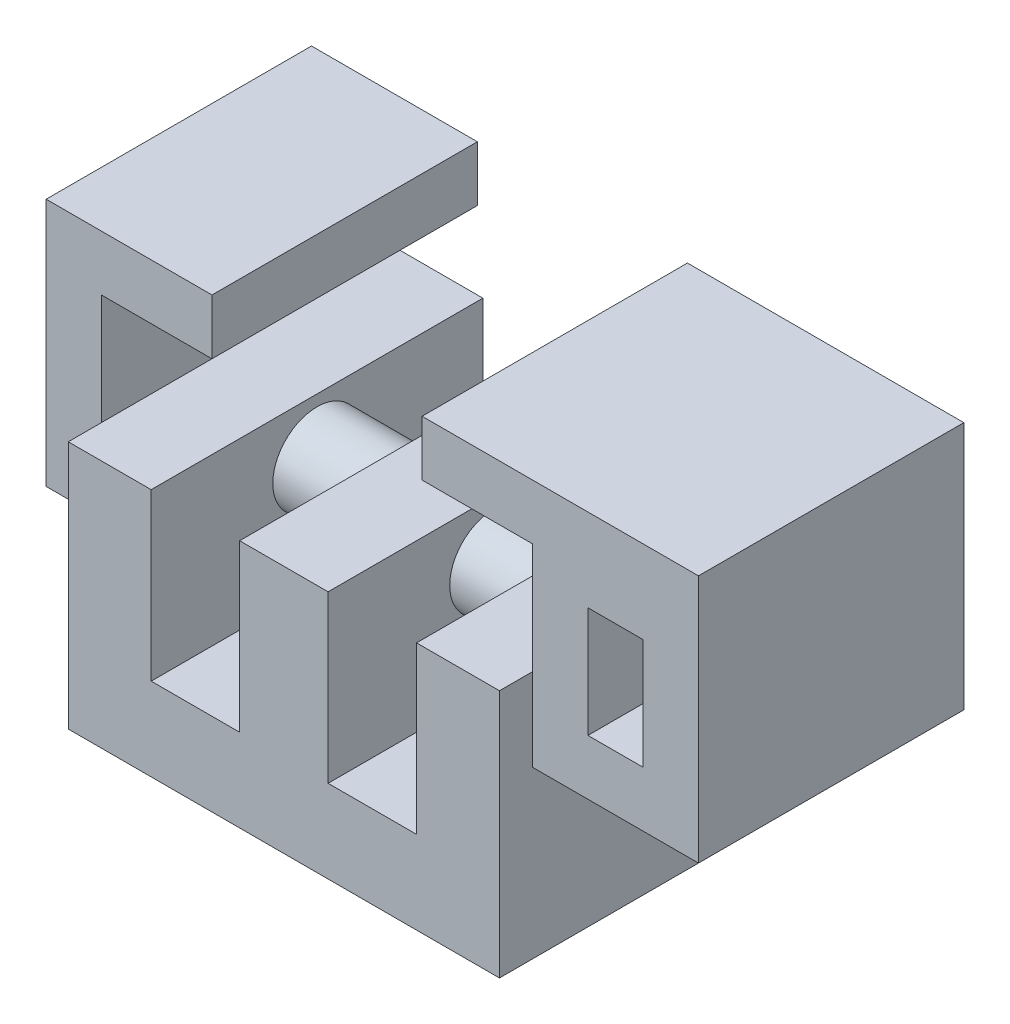
SolidWorks part; units mm, degrees
ref_plane "Plan de face" through (0, 0, 0) normal (0, 0, 1) x (1, 0, 0)
ref_plane "Plan de dessus" through (0, 0, 0) normal (0, 1, 0) x (1, 0, 0)
ref_plane "Plan de droite" through (0, 0, 0) normal (1, 0, 0) x (0, 0, -1)
sketch "Esquisse1" plane through (0, 0, 0) normal (0, 1, 0) x (1, 0, 0)
  line L1 (-19.5, -15) -> (19.5, -15)
  line L2 (-19.5, -15) -> (-19.5, 15)
  line L3 (-19.5, 15) -> (19.5, 15)
  line L4 (19.5, -15) -> (19.5, 15)
  line L5 (-19.5, -15) -> (19.5, 15) construction
  line L6 (-19.5, 15) -> (19.5, -15) construction
  point P0 (0, 0)
  dimension "D1" = 39
  dimension "D2" = 30
extrude "Boss.-Extru.1" add sketch "Esquisse1" along normal blind 7.5 and the other way blind 15
sketch "Esquisse2" plane through (0, 0, 0) normal (0, 1, 0) x (1, 0, 0)
  line L0 (-19.5, 0) -> (-42.4216, 0) construction
  line L1 (-19.5, 15) -> (-19.5, -15) construction
  line L2 (-19.5, 0) -> (-19.5, 12)
  line L3 (-19.5, 12) -> (-24.5, 12)
  line L4 (-24.5, 12) -> (-24.5, -12)
  line L5 (-24.5, -12) -> (-19.5, -12)
  line L6 (-19.5, -12) -> (-19.5, 0)
  line L7 (19.5, 0) -> (36.2396, 0) construction
  line L8 (19.5, -15) -> (19.5, 15) construction
  line L9 (19.5, 0) -> (19.5, 12)
  line L10 (19.5, 12) -> (24.5, 12)
  line L11 (24.5, 12) -> (24.5, -12)
  line L12 (24.5, -12) -> (19.5, -12)
  line L13 (19.5, 0) -> (19.5, -12)
  dimension "D1" = 12
  dimension "D2" = 12
  dimension "D3" = 5
  dimension "D4" = 12
  dimension "D5" = 12
  dimension "D6" = 5
extrude "Boss.-Extru.2" add sketch "Esquisse2" along normal blind 22.5
sketch "Esquisse3" plane through (-19.5, 0, 0) normal (1, 0, 0) x (0, 0, -1)
  line L0 (-12, 22.5) -> (-12, 0) construction
  line L1 (12, 22.5) -> (-12, 22.5)
  line L2 (12, 22.5) -> (12, 17.5)
  line L3 (12, 17.5) -> (-12, 17.5)
  line L4 (-12, 22.5) -> (-12, 17.5)
  dimension "D1" = 5
extrude "Boss.-Extru.3" add sketch "Esquisse3" along normal blind 10
sketch "Esquisse4" plane through (19.5, 0, 0) normal (-1, 0, 0) x (0, 0, 1)
  line L0 (12, 22.5) -> (12, 0) construction
  line L1 (-12, 22.5) -> (12, 22.5)
  line L2 (-12, 22.5) -> (-12, 17.5)
  line L3 (-12, 17.5) -> (12, 17.5)
  line L4 (12, 22.5) -> (12, 17.5)
  dimension "D1" = 5
extrude "Boss.-Extru.4" add sketch "Esquisse4" along normal blind 10
sketch "Esquisse5" plane through (24.5, 0, 0) normal (1, 0, 0) x (0, 0, -1)
  line L5 (-12, 22.5) -> (12, 22.5)
  line L6 (-12, 22.5) -> (-12, 0)
  line L7 (-12, 0) -> (12, 0)
  line L8 (12, 22.5) -> (12, 0)
extrude "Boss.-Extru.5" add sketch "Esquisse5" along normal blind 10
sketch "Esquisse6" plane through (0, 0, -12) normal (0, 0, -1) x (-1, 0, 0)
  line L0 (-34.5, 22.5) -> (-29.5, 22.5) construction
  line L1 (-34.5, 22.5) -> (-9.5, 22.5) construction
  line L2 (-29.5, 22.5) -> (-29.5, 15) construction
  line L4 (-29.5, 15) -> (-24.5, 15)
  line L5 (-29.5, 15) -> (-29.5, 5)
  line L6 (-29.5, 5) -> (-24.5, 5)
  line L7 (-24.5, 15) -> (-24.5, 5)
  dimension "D1" = 5
  dimension "D2" = 5
  dimension "D3" = 7.5
  dimension "D4" = 10
extrude "Enlèv. mat.-Extru.1" cut sketch "Esquisse6" against normal through all
sketch "Esquisse7" plane through (0, 7.5, 0) normal (0, 1, 0) x (1, 0, 0)
  line L0 (-19.5, 15) -> (-12, 15) construction
  line L1 (19.5, 15) -> (-19.5, 15) construction
  line L2 (-12, 15) -> (-4, 15) construction
  line L3 (-4, 15) -> (4, 15) construction
  line L4 (4, 15) -> (12, 15) construction
  line L5 (12, 15) -> (19.5, 15) construction
  line L6 (-19.5, -15) -> (19.5, -15) construction
  line L7 (-12, 15) -> (-4, 15)
  line L8 (-12, 15) -> (-12, -15)
  line L9 (-12, -15) -> (-4, -15)
  line L10 (-4, 15) -> (-4, -15)
  line L12 (4, 15) -> (12, 15)
  line L13 (4, 15) -> (4, -15)
  line L14 (4, -15) -> (12, -15)
  line L15 (12, 15) -> (12, -15)
  dimension "D1" = 7.5
  dimension "D2" = 8
  dimension "D3" = 8
  dimension "D4" = 7.5
extrude "Enlèv. mat.-Extru.2" cut sketch "Esquisse7" against normal blind 15
sketch "Esquisse8" plane through (-12, 0, 0) normal (1, 0, 0) x (0, 0, -1)
  line L0 (0, -7.509) -> (0, 2.491) construction
  circle A1 centre (0, 2.491) radius 4
  dimension "D2" = 8
  dimension "D1" = 10
extrude "Boss.-Extru.6" add sketch "Esquisse8" along normal blind 25
sketch "Esquisse9" plane through (0, -15, 0) normal (0, -1, 0) x (1, 0, 0)
  line L1 (-10, -5) -> (10, -5)
  line L2 (-10, -5) -> (-10, 5)
  line L3 (-10, 5) -> (10, 5)
  line L4 (10, -5) -> (10, 5)
  line L5 (-10, -5) -> (10, 5) construction
  line L6 (-10, 5) -> (10, -5) construction
  point P0 (0, 0)
  dimension "D1" = 20
  dimension "D2" = 10
extrude "Enlèv. mat.-Extru.3" cut sketch "Esquisse9" against normal blind 5
